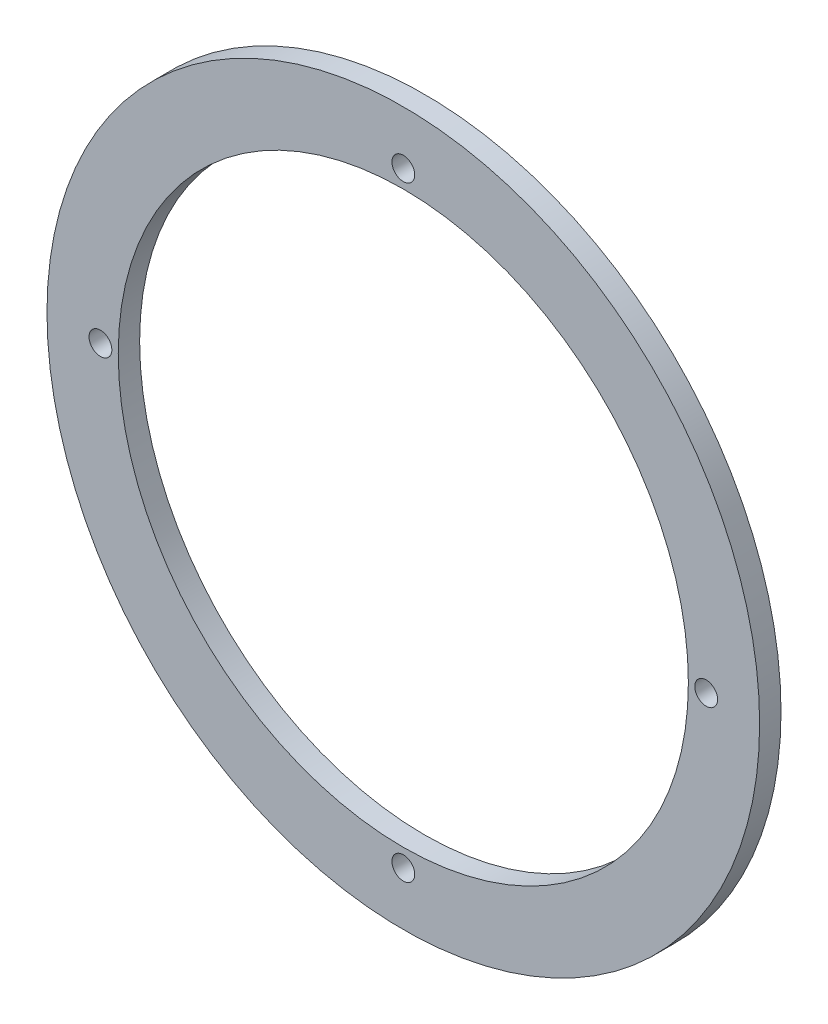
SolidWorks part; units mm, degrees
material "Thornel Mat VMA"
ref_plane "前视基准面" through (0, 0, 0) normal (0, 0, 1) x (1, 0, 0)
ref_plane "上视基准面" through (0, 0, 0) normal (0, 1, 0) x (1, 0, 0)
ref_plane "右视基准面" through (0, 0, 0) normal (1, 0, 0) x (0, 0, -1)
other "Configuration Table"
sketch "草图1" plane through (0, 0, 0) normal (0, 0, 1) x (1, 0, 0)
  circle A0 centre (0, 0) radius 50
  circle A1 centre (0, 0) radius 40
  circle A2 centre (0, 0) radius 42.5 construction
  circle A3 centre (0, 42.5) radius 1.6
  circle A4 centre (42.5, 0) radius 1.6
  circle A5 centre (0, -42.5) radius 1.6
  circle A6 centre (-42.5, 0) radius 1.6
  point P16 (0, 0)
  dimension "D1" = 80
  dimension "D2" = 100
  dimension "D3" = 85
  dimension "D4" = 3.2
  dimension "D5" = 4
extrude "凸台-拉伸1" add sketch "草图1" along normal blind 3
